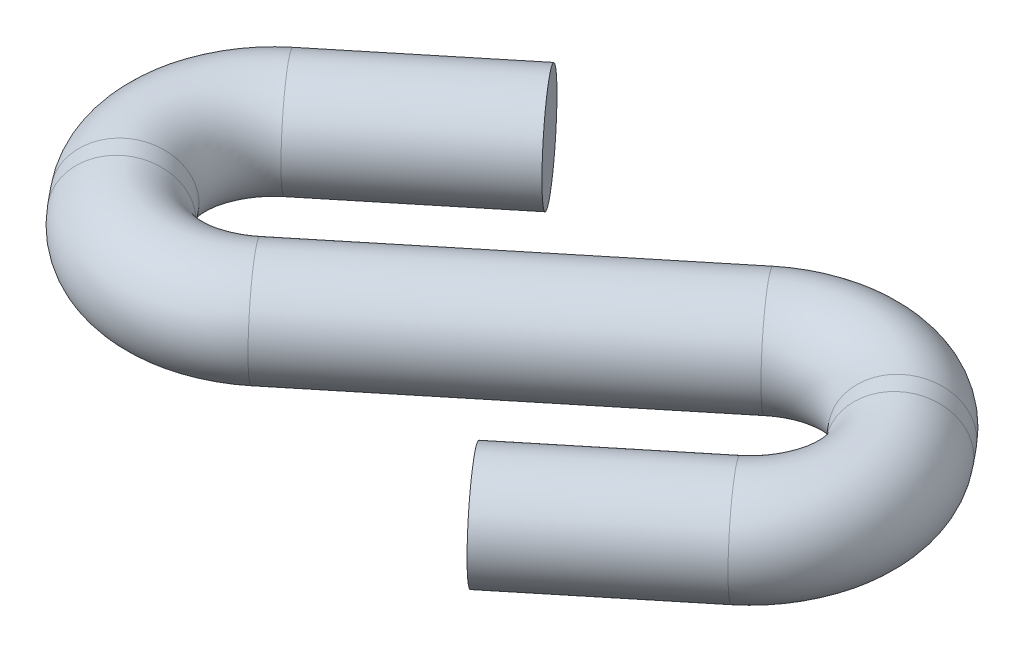
SolidWorks part; units mm, degrees
ref_plane "Front Plane" through (0, 0, 0) normal (0, 0, 1) x (1, 0, 0)
ref_plane "Top Plane" through (0, 0, 0) normal (0, 1, 0) x (1, 0, 0)
ref_plane "Right Plane" through (0, 0, 0) normal (1, 0, 0) x (0, 0, -1)
sketch "Sketch1" plane through (0, 0, 0) normal (0, 1, 0) x (1, 0, 0)
  line L0 (-1.3335, -1.0898) -> (1.3335, 1.0898)
  line L1 (2.7406, 0.9483) -> (2.8672, 0.7935)
  line L2 (2.7257, -0.6136) -> (1.3687, -1.7226)
  line L3 (-2.7406, -0.9483) -> (-2.8672, -0.7935)
  line L4 (-2.7257, 0.6136) -> (-1.3687, 1.7226)
  arc A0 (-1.3335, -1.0898) -> (-2.7406, -0.9483) centre (-1.9663, -0.3155) cw
  arc A1 (1.3335, 1.0898) -> (2.7406, 0.9483) centre (1.9663, 0.3155) cw
  arc A2 (2.8672, 0.7935) -> (2.7257, -0.6136) centre (2.0929, 0.1607) cw
  arc A3 (-2.8672, -0.7935) -> (-2.7257, 0.6136) centre (-2.0929, -0.1607) cw
  point P0 (-1.8276, 2.6738)
  point P3 (0, 0)
  point P10 (-2.1078, -1.7226)
  point P14 (2.1078, 1.7226)
  point P19 (-3.5, -0.0192)
  dimension "D3" = 1
  dimension "D1" = 3.5
  dimension "D2" = 2.2
sweep "Sweep1" add path "Sketch1" circular profile diameter 1 parameters "D3"=1
